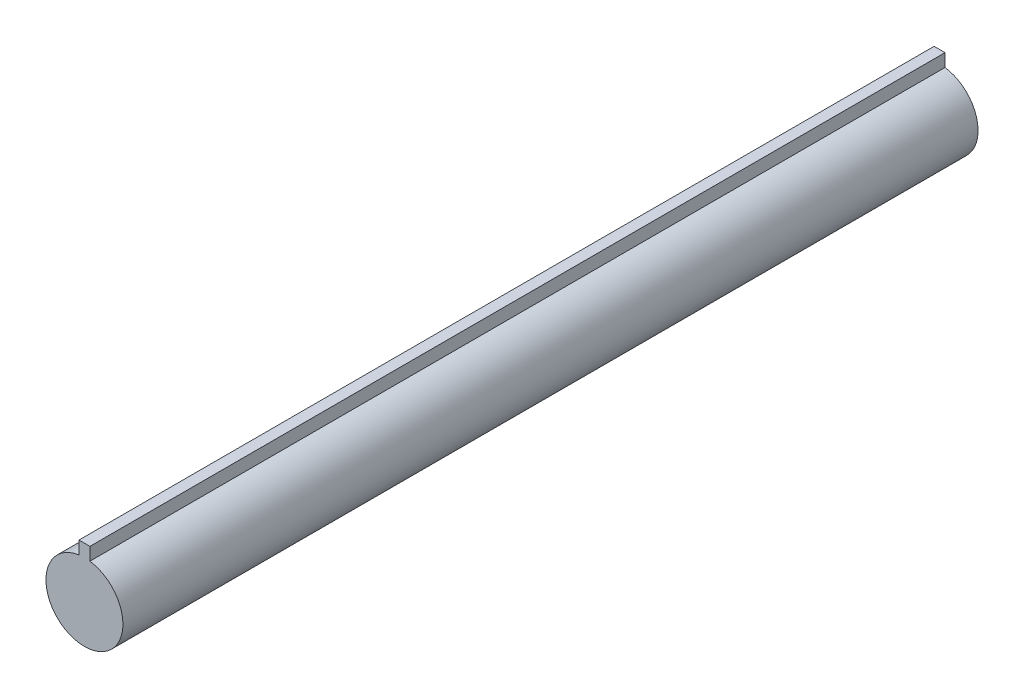
SolidWorks part; units mm, degrees
ref_plane "前视基准面" through (0, 0, 0) normal (0, 0, 1) x (1, 0, 0)
ref_plane "上视基准面" through (0, 0, 0) normal (0, 1, 0) x (1, 0, 0)
ref_plane "右视基准面" through (0, 0, 0) normal (1, 0, 0) x (0, 0, -1)
sketch "草图1" plane through (0, 0, 0) normal (0, 0, 1) x (1, 0, 0)
  line L0 (-5.2592, 0) -> (5.923, 0) construction
  line L1 (0, -5.6781) -> (0, 7.7946) construction
  line L2 (-0.6387, 4.4544) -> (-0.6387, 5.959)
  line L3 (-0.6387, 5.959) -> (0.6387, 5.959)
  line L4 (0.6387, 4.4544) -> (0.6387, 5.959)
  arc A1 (-0.6387, 4.4544) -> (0.6387, 4.4544) centre (0, 0) ccw
  point P12 (0, 5.959)
extrude "凸台-拉伸1" add sketch "草图1" along normal blind 100
